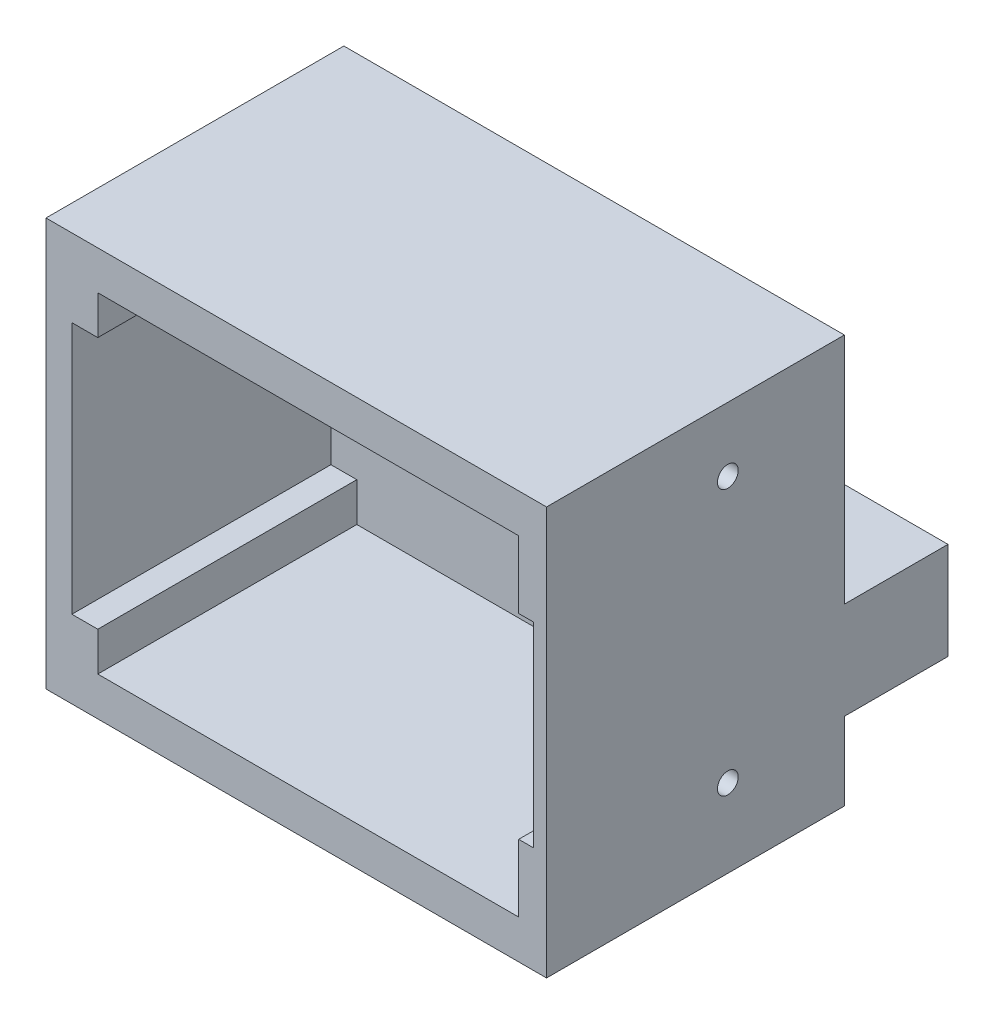
SolidWorks part; units mm, degrees
ref_plane "Front Plane" through (0, 0, 0) normal (0, 0, 1) x (1, 0, 0)
ref_plane "Top Plane" through (0, 0, 0) normal (0, 1, 0) x (1, 0, 0)
ref_plane "Right Plane" through (0, 0, 0) normal (1, 0, 0) x (0, 0, -1)
sketch "Sketch1" plane through (0, 0, 0) normal (0, 1, 0) x (1, 0, 0)
  line L1 (0, 0) -> (38.65, 0)
  line L2 (0, 0) -> (0, 23)
  line L3 (0, 23) -> (38.65, 23)
  line L4 (38.65, 0) -> (38.65, 23)
  dimension "D1" = 38.65
  dimension "D2" = 23
extrude "Boss-Extrude1" add sketch "Sketch1" along normal blind 31.5
sketch "Sketch3" plane through (0, 0, 0) normal (0, 0, 1) x (1, 0, 0)
  line L0 (2, 25.5) -> (2, 6)
  line L1 (2, 6) -> (4, 6)
  line L2 (4, 6) -> (4, 3)
  line L3 (4, 3) -> (36.5, 3)
  line L4 (36.5, 3) -> (36.5, 8.2)
  line L5 (36.5, 8.2) -> (37.65, 8.2)
  line L6 (37.65, 8.2) -> (37.65, 23.3)
  line L7 (37.65, 23.3) -> (36.5, 23.3)
  line L8 (36.5, 23.3) -> (36.5, 28.5)
  line L9 (36.5, 28.5) -> (4, 28.5)
  line L10 (4, 28.5) -> (4, 25.5)
  line L11 (4, 25.5) -> (2, 25.5)
  line L16 (0, 0) -> (38.65, 0)
  line L17 (38.65, 0) -> (38.65, 31.5)
  line L18 (38.65, 31.5) -> (0, 31.5)
  line L19 (0, 31.5) -> (0, 0)
  line L20 (0, 0) -> (38.65, 0)
  line L21 (38.65, 0) -> (38.65, 31.5)
  line L22 (38.65, 31.5) -> (0, 31.5)
  line L23 (0, 31.5) -> (0, 0)
  dimension "D2" = 3
  dimension "D3" = 19.5
  dimension "D4" = 3
  dimension "D5" = 2
  dimension "D6" = 2
  dimension "D7" = 3
  dimension "D8" = 32.5
  dimension "D9" = 1.15
  dimension "D10" = 15.1
  dimension "D11" = 5.2
  dimension "D12" = 31.5
  dimension "D1" = 0
extrude "Cut-Extrude1" cut sketch "Sketch3" against normal blind 20 contours L11 L0 L1 L2 L3 L4 L5 L6 L7 L8 L9 L10
sketch "Sketch4" plane through (36.5, 0, 0) normal (-1, 0, 0) x (0, 0, 1)
  line L0 (0, 3) -> (0, 8.2) construction
  line L1 (0, 8.2) -> (-20, 8.2) construction
  line L2 (-20, 8.2) -> (-20, 3) construction
  line L3 (-20, 3) -> (0, 3) construction
  line L4 (0, 23.3) -> (0, 28.5)
  line L5 (0, 28.5) -> (-20, 28.5)
  line L6 (-20, 28.5) -> (-20, 23.3)
  line L7 (-20, 23.3) -> (0, 23.3)
  line L8 (0, 23.3) -> (0, 28.5)
  line L9 (0, 28.5) -> (-20, 28.5)
  line L10 (-20, 28.5) -> (-20, 23.3)
  line L11 (-20, 23.3) -> (0, 23.3)
  line L12 (0, 8.2) -> (0, 23.3) construction
  line L13 (0, 23.3) -> (-20, 23.3) construction
  line L14 (-20, 23.3) -> (-20, 8.2) construction
  line L15 (-20, 8.2) -> (0, 8.2) construction
  line L16 (0, 3) -> (0, 8.2)
  line L17 (0, 8.2) -> (-20, 8.2)
  line L18 (-20, 8.2) -> (-20, 3)
  line L19 (-20, 3) -> (0, 3)
  line L20 (0, 8.2) -> (0, 23.3)
  line L21 (0, 23.3) -> (-20, 23.3)
  line L22 (-20, 23.3) -> (-20, 8.2)
  line L23 (-20, 8.2) -> (0, 8.2)
  circle A0 centre (-14, 26.55) radius 0.8
  circle A1 centre (-14, 6.05) radius 0.8
  dimension "D5" = 1.6
  dimension "D2" = 20.5
  dimension "D3" = 3.25
  dimension "D4" = 6
  dimension "D1" = 0
extrude "Cut-Extrude2" cut sketch "Sketch4" against normal up to surface (2.15 mm away) contours A0 | A1 up to face at (38.65, 15.75, -11.5)
sketch "Sketch5" plane through (4, 0, 0) normal (1, 0, 0) x (0, 0, -1)
  line L4 (0, 25.5) -> (0, 6)
  line L5 (0, 6) -> (20, 6)
  line L6 (20, 6) -> (20, 25.5)
  line L7 (20, 25.5) -> (0, 25.5)
  line L8 (0, 25.5) -> (0, 6)
  line L9 (0, 6) -> (20, 6)
  line L10 (20, 6) -> (20, 25.5)
  line L11 (20, 25.5) -> (0, 25.5)
  circle A0 centre (17.6, 26.5) radius 0.8
  circle A1 centre (17.6, 6) radius 0.8
  dimension "D3" = 1.6
  dimension "D2" = 20.5
  dimension "D4" = 1
  dimension "D5" = 2.4
  dimension "D1" = 0
extrude "Cut-Extrude3" [suppressed] cut sketch "Sketch5" against normal up to surface (4 mm away) contours A0 | A1
sketch "Sketch6" plane through (0, 0, 0) normal (0, -1, 0) x (1, 0, 0)
  line L0 (38.65, 0) -> (38.65, -23) construction
  line L1 (0, -23) -> (38.65, -23)
  line L2 (0, -23) -> (0, -31)
  line L3 (0, -31) -> (38.65, -31)
  line L4 (38.65, -23) -> (38.65, -31)
  line L5 (0, -27) -> (38.65, -27) construction
  line L6 (37.65, -23) -> (37.65, -31)
  line L7 (0, 0) -> (38.65, 0) construction
  line L8 (38.65, -23) -> (48.65, -23)
  line L9 (38.65, -23) -> (38.65, 0)
  line L10 (38.65, 0) -> (48.65, 0)
  line L11 (48.65, -23) -> (48.65, 0)
  line L12 (43.65, 0) -> (43.65, -23) construction
  circle A0 centre (29.65, -27) radius 1.5
  circle A1 centre (8, -27) radius 1.5
  circle A2 centre (43.65, -5.5) radius 1.5
  circle A3 centre (43.65, -17.5) radius 1.5
  line M14 (0, -23) -> (38.65, -23)
  dimension "D3" = 3
  dimension "D7" = 3
  dimension "D1" = 8
  dimension "D2" = 1
  dimension "D4" = 8
  dimension "D5" = 8
  dimension "D6" = 10
  dimension "D8" = 5.5
  dimension "D9" = 5.5
extrude "Boss-Extrude2" add sketch "Sketch6" against normal blind 7.5 from offset 6 contours L6 L2 L3 A1 A0 M14 | L1 L6 L3 L4
